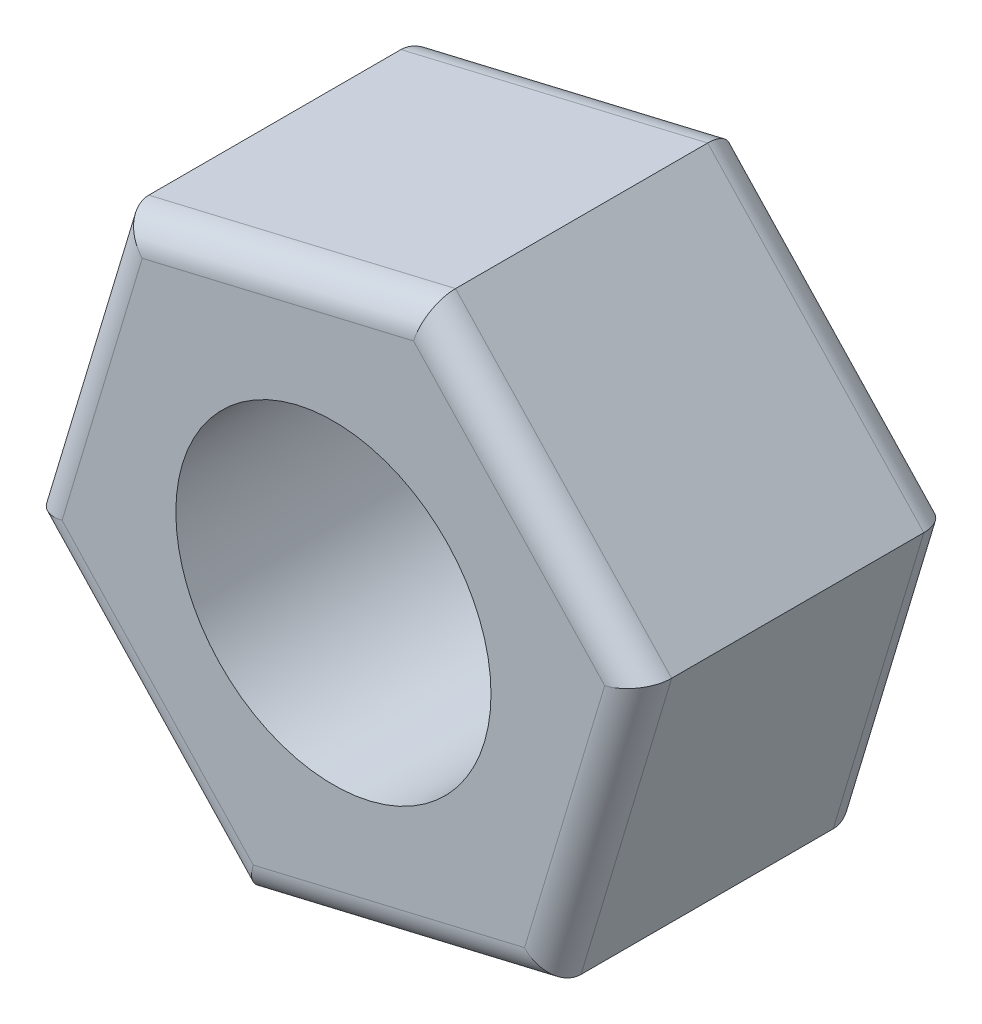
SolidWorks part; units mm, degrees
ref_plane "Спереди" through (0, 0, 0) normal (0, 0, 1) x (1, 0, 0)
ref_plane "Сверху" through (0, 0, 0) normal (0, 1, 0) x (1, 0, 0)
ref_plane "Справа" through (0, 0, 0) normal (1, 0, 0) x (0, 0, -1)
sketch "Эскиз1" plane through (0, 0, 0) normal (0, 0, 1) x (1, 0, 0)
  line L1 (9.7323, 2.2983) -> (2.8757, 9.5776)
  line L2 (2.8757, 9.5776) -> (-6.8566, 7.2793)
  line L3 (-6.8566, 7.2793) -> (-9.7323, -2.2983)
  line L4 (-9.7323, -2.2983) -> (-2.8757, -9.5776)
  line L5 (-2.8757, -9.5776) -> (6.8566, -7.2793)
  line L6 (6.8566, -7.2793) -> (9.7323, 2.2983)
  circle A0 centre (0, 0) radius 5
  circle A1 centre (0, 0) radius 8.6603 construction
extrude "Вытянуть1" add sketch "Эскиз1" along normal blind 10
fillet "Скругление1" radius 1 12 edges at (-8.2944, 2.4905, 10) (-6.304, -5.938, 10) (1.9904, -8.4284, 10) (8.2944, -2.4905, 10) (6.304, 5.938, 10) (-1.9904, 8.4284, 10) (-8.2944, 2.4905, 0) (-6.304, -5.938, 0) (1.9904, -8.4284, 0) (8.2944, -2.4905, 0) (6.304, 5.938, 0) (-1.9904, 8.4284, 0)
